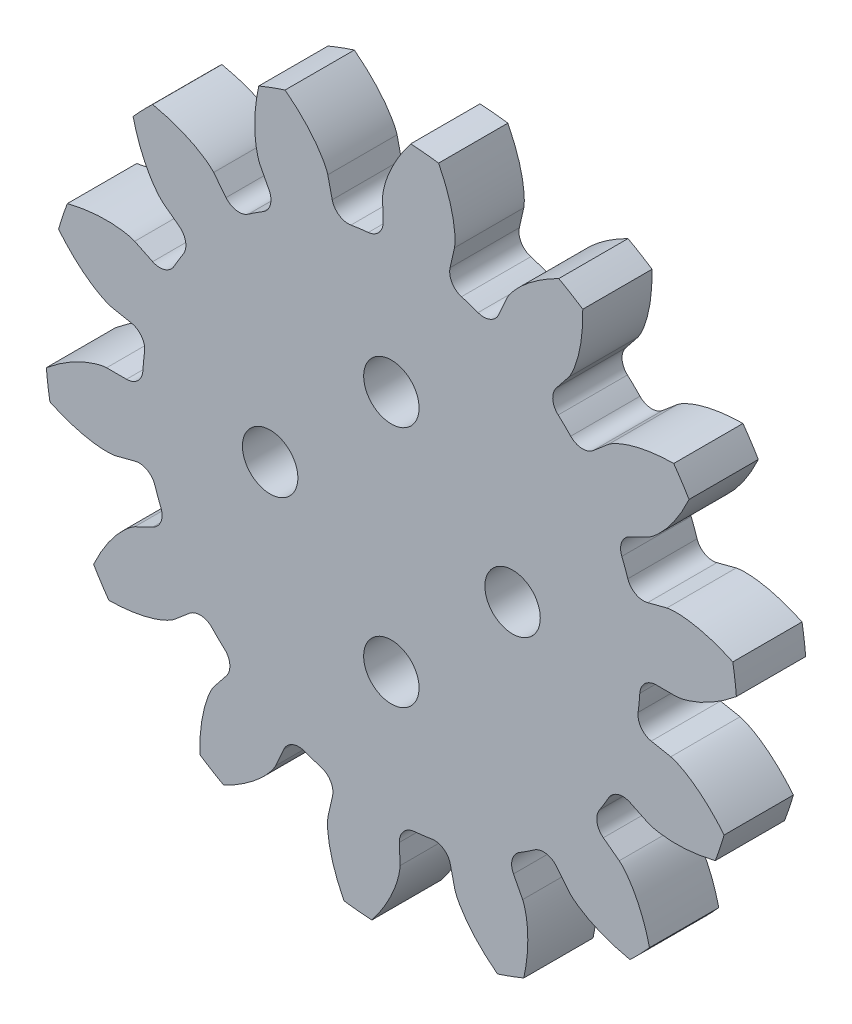
SolidWorks part; units mm, degrees
ref_plane "前基準面" through (0, 0, 0) normal (0, 0, 1) x (1, 0, 0)
ref_plane "上基準面" through (0, 0, 0) normal (0, 1, 0) x (1, 0, 0)
ref_plane "右基準面" through (0, 0, 0) normal (1, 0, 0) x (0, 0, -1)
sketch "草圖1" plane through (0, 0, 0) normal (0, 0, 1) x (1, 0, 0)
  spline S0 degree 4 poles (16.4446, 0) (16.4521, 0.0001) (16.4731, 0.0009) (16.5129, 0.0038) (16.5775, 0.0107) (16.6596, 0.0227) (16.7654, 0.0418) (16.8893, 0.0689) (17.0247, 0.1036) (17.1711, 0.1466) (17.3162, 0.1941) (17.46, 0.2456) (17.6023, 0.3008) (17.7735, 0.3721) (17.977, 0.4638) (18.2121, 0.5798) (18.4752, 0.7219) (18.7393, 0.8777) (18.9957, 1.04) (19.2505, 1.2142) (19.4939, 1.3899) (19.7419, 1.5825) (19.9684, 1.7655) (20.2164, 1.9815) (20.415, 2.159) (20.6705, 2.4046) (20.8194, 2.5531) (20.9915, 2.7308) (21.0666, 2.8117) (21.113, 2.8615) knots 0 0 0 0 0 0.005377 0.015084 0.028532 0.04661 0.064855 0.092111 0.119476 0.146842 0.174209 0.201575 0.228941 0.256307 0.307035 0.361767 0.4165 0.471232 0.525964 0.580697 0.635429 0.690161 0.744894 0.799626 0.854358 0.909091 0.954545 1 1 1 1 1 construction
  spline S1 degree 4 poles (16.4446, 0) (16.4521, 0.0001) (16.4731, 0.0009) (16.5129, 0.0038) (16.5775, 0.0107) (16.6596, 0.0227) (16.7654, 0.0418) (16.8893, 0.0689) (17.0247, 0.1036) (17.1711, 0.1466) (17.3162, 0.1941) (17.46, 0.2456) (17.6023, 0.3008) (17.7735, 0.3721) (17.977, 0.4638) (18.2121, 0.5798) (18.4752, 0.7219) (18.7393, 0.8777) (18.9957, 1.04) (19.2505, 1.2142) (19.4939, 1.3899) (19.7419, 1.5825) (19.9684, 1.7655) (20.2164, 1.9815) (20.415, 2.159) (20.6151, 2.3514) (20.7117, 2.4463) (20.7608, 2.4954) knots 0 0 0 0 0 0.005377 0.015084 0.028532 0.04661 0.064855 0.092111 0.119476 0.146842 0.174209 0.201575 0.228941 0.256307 0.307035 0.361767 0.4165 0.471232 0.525964 0.580697 0.635429 0.690161 0.744894 0.799626 0.854358 0.909091 0.909091 0.909091 0.909091 0.909091
sketch "草圖2" plane through (0, 0, 0) normal (0, 0, 1) x (1, 0, 0)
  line L0 (0, 0) -> (26.7696, 0) construction
  line L1 (0, 0) -> (17.4176, -1.6965) construction
  line L2 (16.4446, 0) -> (14.375, 0)
  line L3 (16.1355, -3.1734) -> (14.1048, -2.774)
  circle A0 centre (0, 0) radius 16.445
  circle A1 centre (0, 0) radius 14.375
  circle A2 centre (0, 0) radius 20
  arc A3 (17.4176, -1.6965) -> (17.4981, 0.2608) centre (0, 0) ccw
  spline S0 degree 4 poles (-9.671, 1999.7247) (14.0095, 25.6843) (14.8621, 0.3959) (15.735, -0.0794) (16.5775, 0.0107) (16.6596, 0.0227) (16.7654, 0.0418) (16.8893, 0.0689) (17.0247, 0.1036) (17.1711, 0.1466) (17.3162, 0.1941) (17.46, 0.2456) (17.6023, 0.3008) (17.7735, 0.3721) (17.977, 0.4638) (18.2121, 0.5798) (18.4752, 0.7219) (18.7393, 0.8777) (18.9957, 1.04) (19.2505, 1.2142) (19.4939, 1.3899) (19.7419, 1.5825) (19.9684, 1.7655) (20.2164, 1.9815) (21.2256, 2.8839) (24.3108, 6.2006) (-16.6725, -34.3486) (1434.3227, 1417.2657) knots -0.560827 -0.560827 -0.560827 -0.560827 -0.560827 0.005377 0.015084 0.028532 0.04661 0.064855 0.092111 0.119476 0.146842 0.174209 0.201575 0.228941 0.256307 0.307035 0.361767 0.4165 0.471232 0.525964 0.580697 0.635429 0.690161 0.744894 0.799626 0.854358 1.8029 1.8029 1.8029 1.8029 1.8029 only from (16.4446, 0) to (20.7608, 2.4954) construction
  spline S1 degree 4 poles (16.4446, 0) (16.4521, 0.0001) (16.4731, 0.0009) (16.5129, 0.0038) (16.5775, 0.0107) (16.6596, 0.0227) (16.7654, 0.0418) (16.8893, 0.0689) (17.0247, 0.1036) (17.1711, 0.1466) (17.3162, 0.1941) (17.46, 0.2456) (17.6023, 0.3008) (17.7735, 0.3721) (17.977, 0.4638) (18.2121, 0.5798) (18.4752, 0.7219) (18.7393, 0.8777) (18.9957, 1.04) (19.2505, 1.2142) (19.4939, 1.3899) (19.7419, 1.5825) (19.9684, 1.7655) (20.2164, 1.9815) (20.415, 2.159) (20.6151, 2.3514) (20.7117, 2.4463) (20.7608, 2.4954) knots 0 0 0 0 0 0.005377 0.015084 0.028532 0.04661 0.064855 0.092111 0.119476 0.146842 0.174209 0.201575 0.228941 0.256307 0.307035 0.361767 0.4165 0.471232 0.525964 0.580697 0.635429 0.690161 0.744894 0.799626 0.854358 0.909091 0.909091 0.909091 0.909091 0.909091
  spline S2 degree 4 poles (16.1355, -3.1734) (16.1429, -3.1749) (16.1634, -3.1797) (16.2017, -3.1902) (16.2638, -3.2095) (16.3421, -3.2371) (16.4422, -3.2763) (16.5585, -3.3268) (16.6847, -3.387) (16.8201, -3.4574) (16.9533, -3.532) (17.0845, -3.6103) (17.2134, -3.6919) (17.3676, -3.7949) (17.5496, -3.9241) (17.7579, -4.0834) (17.9886, -4.2736) (18.2177, -4.4774) (18.438, -4.6862) (18.6543, -4.9062) (18.8593, -5.1255) (19.0654, -5.3624) (19.2523, -5.5857) (19.4541, -5.8455) (19.6146, -6.058) (19.7738, -6.2853) (19.8503, -6.3972) (19.889, -6.4548) knots 0 0 0 0 0 0.005377 0.015084 0.028532 0.04661 0.064855 0.092111 0.119476 0.146842 0.174209 0.201575 0.228941 0.256307 0.307035 0.361767 0.4165 0.471232 0.525964 0.580697 0.635429 0.690161 0.744894 0.799626 0.854358 0.909091 0.909091 0.909091 0.909091 0.909091
  dimension "D1" = 35
  dimension "D2" = 40
  dimension "D3" = 28.75
  dimension "D4" = 32.89
  dimension "D5" = 1.96
extrude "填料-伸長1" add sketch "草圖2" along normal blind 4 contours A2
sketch "草圖3" plane through (0, 0, 4) normal (0, 0, 1) x (1, 0, 0)
  line L0 (16.1355, -3.1734) -> (14.1048, -2.774) construction
  line L1 (16.4446, 0) -> (14.375, 0) construction
  line L2 (16.1355, -3.1734) -> (14.1048, -2.774)
  line L3 (16.4446, 0) -> (14.375, 0)
  circle A0 centre (0, 0) radius 14.375 construction
  circle A1 centre (0, 0) radius 20 construction
  arc A2 (14.1048, -2.774) -> (14.375, 0) centre (0, 0) ccw
  arc A3 (19.2161, -5.5446) -> (19.9248, 1.7322) centre (0, 0) ccw
  spline S0 degree 4 poles (-395.3821, -1960.2718) (8.7898, -27.905) (14.5064, -3.2565) (15.4545, -2.9585) (16.2638, -3.2095) (16.3421, -3.2371) (16.4422, -3.2763) (16.5585, -3.3268) (16.6847, -3.387) (16.8201, -3.4574) (16.9533, -3.532) (17.0845, -3.6103) (17.2134, -3.6919) (17.3676, -3.7949) (17.5496, -3.9241) (17.7579, -4.0834) (17.9886, -4.2736) (18.2177, -4.4774) (18.438, -4.6862) (18.6543, -4.9062) (18.8593, -5.1255) (19.0654, -5.3624) (19.2523, -5.5857) (19.4541, -5.8455) (20.2701, -6.9256) (22.6573, -10.7753) (-9.7307, 36.9203) (1133.8693, -1667.4124) knots -0.560827 -0.560827 -0.560827 -0.560827 -0.560827 0.005377 0.015084 0.028532 0.04661 0.064855 0.092111 0.119476 0.146842 0.174209 0.201575 0.228941 0.256307 0.307035 0.361767 0.4165 0.471232 0.525964 0.580697 0.635429 0.690161 0.744894 0.799626 0.854358 1.8029 1.8029 1.8029 1.8029 1.8029 only from (16.1355, -3.1734) to (19.889, -6.4548) construction
  spline S1 degree 4 poles (-9.671, 1999.7247) (14.0095, 25.6843) (14.8621, 0.3959) (15.735, -0.0794) (16.5775, 0.0107) (16.6596, 0.0227) (16.7654, 0.0418) (16.8893, 0.0689) (17.0247, 0.1036) (17.1711, 0.1466) (17.3162, 0.1941) (17.46, 0.2456) (17.6023, 0.3008) (17.7735, 0.3721) (17.977, 0.4638) (18.2121, 0.5798) (18.4752, 0.7219) (18.7393, 0.8777) (18.9957, 1.04) (19.2505, 1.2142) (19.4939, 1.3899) (19.7419, 1.5825) (19.9684, 1.7655) (20.2164, 1.9815) (21.2256, 2.8839) (24.3108, 6.2006) (-16.6725, -34.3486) (1434.3227, 1417.2657) knots -0.560827 -0.560827 -0.560827 -0.560827 -0.560827 0.005377 0.015084 0.028532 0.04661 0.064855 0.092111 0.119476 0.146842 0.174209 0.201575 0.228941 0.256307 0.307035 0.361767 0.4165 0.471232 0.525964 0.580697 0.635429 0.690161 0.744894 0.799626 0.854358 1.8029 1.8029 1.8029 1.8029 1.8029 only from (16.4446, 0) to (20.7608, 2.4954) construction
  spline S2 degree 4 poles (16.1355, -3.1734) (16.1429, -3.1749) (16.1634, -3.1797) (16.2017, -3.1902) (16.2638, -3.2095) (16.3421, -3.2371) (16.4422, -3.2763) (16.5585, -3.3268) (16.6847, -3.387) (16.8201, -3.4574) (16.9533, -3.532) (17.0845, -3.6103) (17.2134, -3.6919) (17.3676, -3.7949) (17.5496, -3.9241) (17.7579, -4.0834) (17.9886, -4.2736) (18.2177, -4.4774) (18.438, -4.6862) (18.6543, -4.9062) (18.8593, -5.1255) (19.0292, -5.3208) (19.1392, -5.4509) (19.2017, -5.527) (19.2161, -5.5446) knots 0 0 0 0 0 0.005377 0.015084 0.028532 0.04661 0.064855 0.092111 0.119476 0.146842 0.174209 0.201575 0.228941 0.256307 0.307035 0.361767 0.4165 0.471232 0.525964 0.580697 0.635429 0.690161 0.706457 0.706457 0.706457 0.706457 0.706457
  spline S3 degree 4 poles (16.4446, 0) (16.4521, 0.0001) (16.4731, 0.0009) (16.5129, 0.0038) (16.5775, 0.0107) (16.6596, 0.0227) (16.7654, 0.0418) (16.8893, 0.0689) (17.0247, 0.1036) (17.1711, 0.1466) (17.3162, 0.1941) (17.46, 0.2456) (17.6023, 0.3008) (17.7735, 0.3721) (17.977, 0.4638) (18.2121, 0.5798) (18.4752, 0.7219) (18.7393, 0.8777) (18.9957, 1.04) (19.2505, 1.2142) (19.4939, 1.3899) (19.6983, 1.5487) (19.8313, 1.6551) (19.9073, 1.7177) (19.9248, 1.7322) knots 0 0 0 0 0 0.005377 0.015084 0.028532 0.04661 0.064855 0.092111 0.119476 0.146842 0.174209 0.201575 0.228941 0.256307 0.307035 0.361767 0.4165 0.471232 0.525964 0.580697 0.635429 0.690161 0.706457 0.706457 0.706457 0.706457 0.706457
extrude "除料-伸長1" cut sketch "草圖3" against normal blind 4
fillet "圓角1" radius 0.95 2 edges at (14.1048, -2.774, 2) (14.375, 0, 2)
pattern_circular "環狀複製排列1" count 14 every 25.71 about axis through (0, 0, 4) along (0, 0, -1) of "圓角1", "除料-伸長1"
sketch "草圖4" plane through (0, 0, 4) normal (0, 0, 1) x (1, 0, 0)
  line L0 (0, 0) -> (27.4941, 0) construction
  circle A0 centre (7, 0) radius 1.6
  dimension "D1" = 3.2
  dimension "D2" = 7
extrude "除料-伸長2" cut sketch "草圖4" against normal blind 4
pattern_circular "環狀複製排列2" count 4 every 90 about axis through (0, 0, 0) along (0, 0, 1) of "除料-伸長2"
sketch "草圖5" plane through (0, 0, 4) normal (0, 0, 1) x (1, 0, 0)
  circle A0 centre (0, 0) radius 17.5 construction
  dimension "D1" = 35
equation "\"a\"= 20"
equation "\"M\"= 2.5"
equation "\"T\"= 14"
equation "\"R\"= 0.38 * \"M\""
equation "\"D\"= \"M\" * \"T\""
equation "\"Da\"= ( \"T\" + 2 ) * \"M\""
equation "\"Df\"= ( \"T\" - 2.5 ) * \"M\""
equation "\"Db\"= \"M\" * \"T\" * cos ( \"a\" )"
equation "\"rb\"= \"Db\" / 2"
equation "\"S\"= pi * \"M\" * 0.5"
